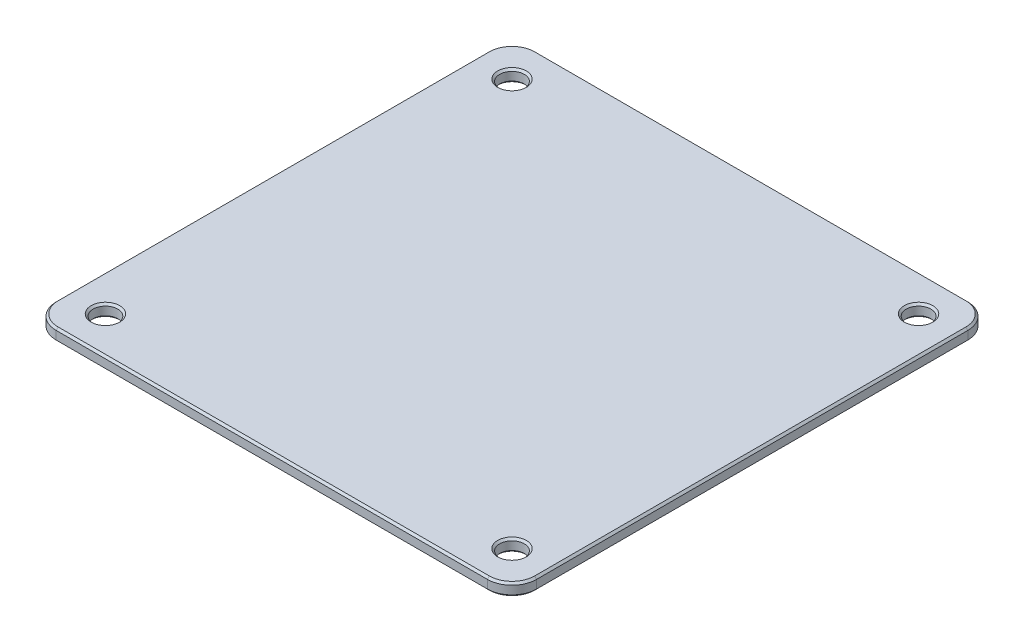
SolidWorks part; units mm, degrees
ref_plane "Front" through (0, 0, 0) normal (0, 0, 1) x (1, 0, 0)
ref_plane "Top" through (0, 0, 0) normal (0, 1, 0) x (1, 0, 0)
ref_plane "Right" through (0, 0, 0) normal (1, 0, 0) x (0, 0, -1)
sketch "Sketch2" plane through (0, 0, 0) normal (0, 1, 0) x (1, 0, 0)
  line L0 (26.1937, -26.1937) -> (26.1937, 26.1938) construction
  line L1 (-30.9563, -30.9562) -> (30.9562, -30.9562)
  line L2 (-30.9563, -30.9562) -> (-30.9563, 30.9563)
  line L3 (-30.9563, 30.9563) -> (30.9562, 30.9563)
  line L4 (30.9562, -30.9562) -> (30.9562, 30.9563)
  line L5 (-30.9563, -30.9562) -> (30.9562, 30.9563) construction
  line L6 (-30.9563, 30.9563) -> (30.9562, -30.9562) construction
  line L7 (26.1937, 26.1938) -> (-26.1937, 26.1937) construction
  line L8 (-26.1937, 26.1937) -> (-26.1937, -26.1937) construction
  line L9 (-26.1937, -26.1937) -> (26.1937, -26.1937) construction
  line L10 (26.1937, 26.1938) -> (30.9562, 26.1938) construction
  line L11 (26.1937, 26.1938) -> (26.1937, 30.9563) construction
  circle A0 centre (-26.1937, 26.1937) radius 1.5875
  circle A1 centre (26.1937, 26.1938) radius 1.5875
  circle A2 centre (26.1937, -26.1937) radius 1.5875
  circle A3 centre (-26.1937, -26.1937) radius 1.5875
  point P0 (0, 0)
  dimension "D3" = 3.175
  dimension "D1" = 61.9125
  dimension "D2" = 4.7625
extrude "Boss-Extrude1" add sketch "Sketch2" along normal blind 1.5875 contours L3 L4 L1 L2
fillet "Fillet1" radius 3.175 4 edges at (30.9562, 0.7937, 30.9562) (-30.9563, 0.7937, -30.9563) (30.9562, 0.7937, -30.9563) (-30.9563, 0.7937, 30.9562)
chamfer "Chamfer1" distance 0.254 angle 45 24 edges at (-26.1937, 0, 27.7812) (26.1937, 0, -24.6063) (30.0263, 0, -30.0263) (0, 0, -30.9563) (-30.0263, 0, -30.0263) (-30.9563, 0, 0) (-30.0263, 0, 30.0263) (0, 0, 30.9562) (30.0263, 0, 30.0263) (30.9562, 0, 0) (-26.1937, 0, -24.6062) (26.1937, 0, 27.7812) (-26.1937, 1.5875, 27.7812) (26.1937, 1.5875, 27.7812) (26.1937, 1.5875, -24.6063) (-26.1937, 1.5875, -24.6062) (-30.0263, 1.5875, 30.0263) (-30.9563, 1.5875, 0) (-30.0263, 1.5875, -30.0263) (0, 1.5875, -30.9563) (30.0263, 1.5875, -30.0263) (30.9562, 1.5875, 0) (30.0263, 1.5875, 30.0263) (0, 1.5875, 30.9562)
